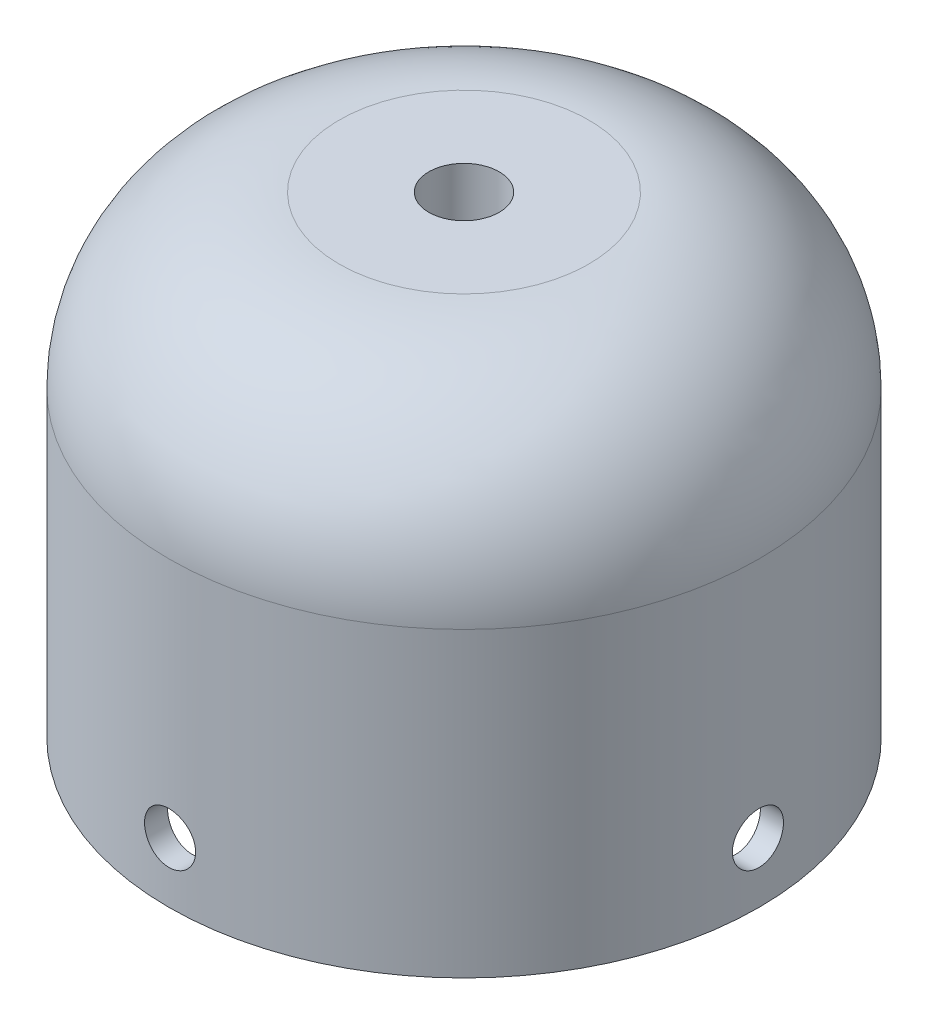
SolidWorks part; units mm, degrees
material "6061-T6 (SS)"
ref_plane "Front Plane" through (0, 0, 0) normal (0, 0, 1) x (1, 0, 0)
ref_plane "Top Plane" through (0, 0, 0) normal (0, 1, 0) x (1, 0, 0)
ref_plane "Right Plane" through (0, 0, 0) normal (1, 0, 0) x (0, 0, -1)
sketch "Sketch1" plane through (0, 0, 0) normal (1, 0, 0) x (0, 0, -1)
  line L0 (0, 42.1571) -> (0, -43.9027) construction
  line L1 (-23.775, -26.8) -> (-23.775, -16.55) construction
  line L2 (-26, 26.8) -> (26, 26.8) construction
  line L4 (-26, -26.8) -> (26, -26.8) construction
  line L5 (26, 26.8) -> (26, -26.8) construction
  line L6 (-26, 26.8) -> (26, -26.8) construction
  line L7 (-26, -26.8) -> (26, 26.8) construction
  line L17 (0, 26.8) -> (0, -26.8)
  line L19 (-23.775, -26.8) -> (-26, -26.8)
  line L22 (-23.775, -16.55) -> (-23.025, -15.8) construction
  line L23 (-23.025, -15.8) -> (-23.025, -1) construction
  line L24 (-23.025, -1) -> (-22.025, 0) construction
  line L25 (-22.025, 0) -> (-8.475, 0) construction
  line L28 (-8.475, 0) -> (-3.1, 0) construction
  line L29 (-3.1, 0) -> (-3.1, 15) construction
  line L30 (-26, -26.8) -> (-26, 15)
  line L31 (-26, 15) -> (-3.1, 15)
  line L32 (-23.975, -26.8) -> (-23.975, -16.4672)
  line L33 (-23.975, -16.4672) -> (-23.225, -15.7172)
  line L34 (-23.225, -15.7172) -> (-23.225, -0.9172)
  line L35 (-23.225, -0.9172) -> (-22.1078, 0.2)
  line L36 (-22.1078, 0.2) -> (-8.475, 0.2)
  line L37 (-8.475, 0.2) -> (-3.1, 0.2)
  line L38 (-3.1, 0.2) -> (-3.1, 15)
  point P3 (0, 0)
  dimension "D1" = 3.1
  dimension "D2" = 52
  dimension "D3" = 23.775
  dimension "D4" = 0.75
  dimension "D5" = 15.8
  dimension "D6" = 45
  dimension "D7" = 1
  dimension "D8" = 11
  dimension "D9" = 45
  dimension "D10" = 15
  dimension "D11" = 0.2
revolve "Revolve2" add sketch "Sketch1" angle 360 about L0
ref_plane "Plane1" through (-26, 0, 0) normal (-1, 0, 0) x (0, 0, 1)
sketch "Sketch5" plane through (0, 0, 0) normal (0, 0, 1) x (1, 0, 0)
  line L2 (-26, 15) -> (-11, 15)
  line L3 (-26, 15) -> (-26, 0)
  line L4 (0, 20) -> (0, 0) construction
  line L6 (26, 15) -> (-26, 15) construction
  arc A0 (-26, 0) -> (-11, 15) centre (-11, 0) cw
  dimension "D1" = 11
  dimension "D2" = 26
revolve "Cut-Revolve1" cut sketch "Sketch5" angle 360 about L4
sketch "Sketch6" plane through (-26, 0, 0) normal (-1, 0, 0) x (0, 0, 1)
  line L1 (-26, -26.8) -> (26, -26.8) construction
  circle A0 centre (0, -21.3) radius 2.25
  dimension "D1" = 4.5
  dimension "D2" = 5.5
extrude "Cut-Extrude1" cut sketch "Sketch6" against normal blind 10
pattern_circular "CirPattern1" count 4 over 360 about axis through (0, -26.8, 0) along (0, 1, 0) of "Cut-Extrude1"
sketch "Sketch7" plane through (0, -26.8, 0) normal (0, -1, 0) x (1, 0, 0)
  circle A0 centre (0, 0) radius 26 construction
  circle A1 centre (0, 0) radius 26
extrude "Cut-Extrude2" cut sketch "Sketch7" against normal blind 0.2
sketch "Sketch8" plane through (0, 0.2, 0) normal (0, -1, 0) x (1, 0, 0)
  circle A0 centre (0, 0) radius 10.25 construction
  circle A1 centre (0, 0) radius 11.55
  circle A2 centre (0, 0) radius 8.95
  dimension "D1" = 20.5
  dimension "D2" = 1.3
  dimension "D3" = 1.3
extrude "Cut-Extrude3" cut sketch "Sketch8" against normal blind 1.3
fillet "Fillet1" radius 0.3 2 edges at (0, 1.5, -8.95) (0, 1.5, -11.55)
